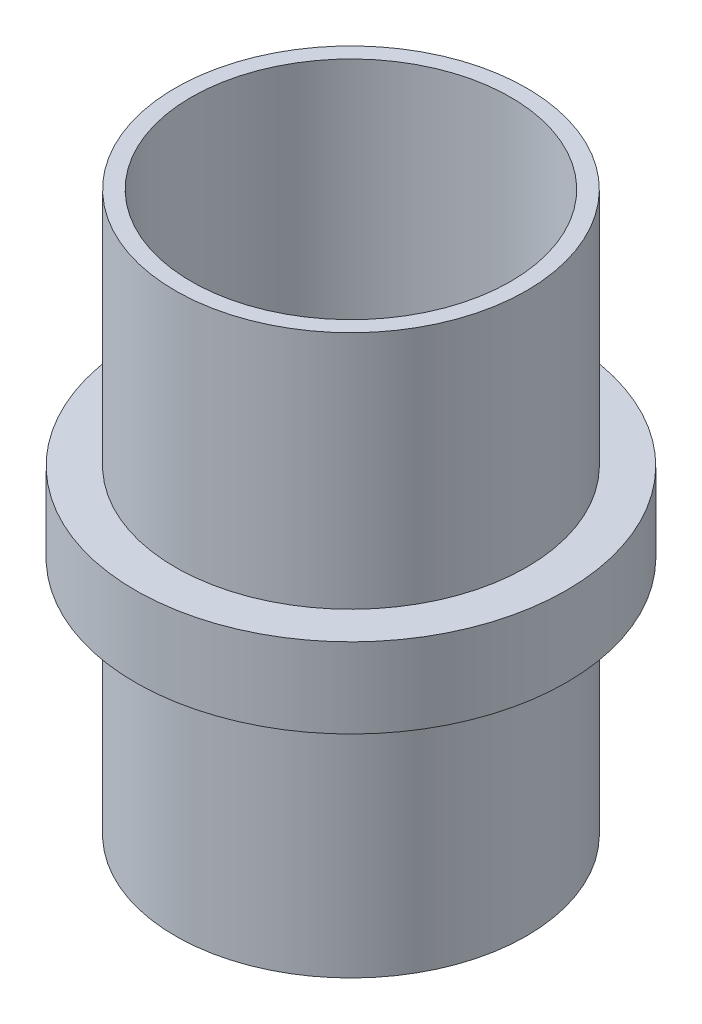
SolidWorks part; units mm, degrees
ref_plane "Front Plane" through (0, 0, 0) normal (0, 0, 1) x (1, 0, 0)
ref_plane "Top Plane" through (0, 0, 0) normal (0, 1, 0) x (1, 0, 0)
ref_plane "Right Plane" through (0, 0, 0) normal (1, 0, 0) x (0, 0, -1)
sketch "Sketch1" plane through (0, 0, 0) normal (0, 0, 1) x (1, 0, 0)
  line L0 (0, -17.5) -> (0, 17.5) construction
  line L1 (10, 17.5) -> (10, 2.5)
  line L3 (9, -2.5) -> (9, -17.5)
  line L6 (11, 17.5) -> (11, 2.5)
  line L7 (11, -17.5) -> (9, -17.5)
  line L8 (11, 17.5) -> (10, 17.5)
  line L9 (9, -2.5) -> (10, 2.5)
  line L10 (11, -2.5) -> (11, -17.5)
  line L11 (11, 2.5) -> (13.5, 2.5)
  line L13 (11, -2.5) -> (13.5, -2.5)
  line L14 (13.5, 2.5) -> (13.5, -2.5)
  point P4 (0, 0)
  point P15 (13.5, 0)
  dimension "D1" = 35
  dimension "D2" = 10
  dimension "D3" = 18
  dimension "D4" = 15
  dimension "D5" = 15
  dimension "D6" = 5
  dimension "D7" = 2.5
  dimension "D8" = 22
revolve "Revolve1" add sketch "Sketch1" angle 360 about L0
